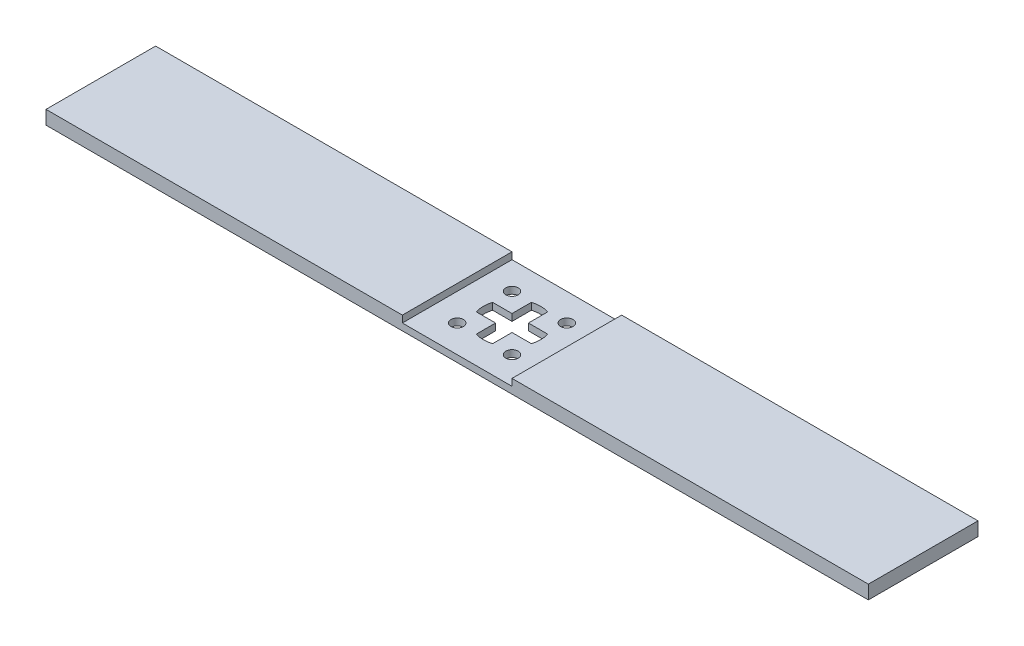
SolidWorks part; units mm, degrees
ref_plane "Front Plane" through (0, 0, 0) normal (0, 0, 1) x (1, 0, 0)
ref_plane "Top Plane" through (0, 0, 0) normal (0, 1, 0) x (1, 0, 0)
ref_plane "Right Plane" through (0, 0, 0) normal (1, 0, 0) x (0, 0, -1)
sketch "Sketch1" plane through (0, 0, 0) normal (0, 1, 0) x (1, 0, 0)
  line L0 (0, -32.4512) -> (0, 39.5498) construction
  line L1 (-150, 20) -> (150, 20)
  line L2 (-150, 20) -> (-150, -20)
  line L3 (-150, -20) -> (150, -20)
  line L4 (150, 20) -> (150, -20)
  line L5 (-150, 20) -> (150, -20) construction
  line L6 (-150, -20) -> (150, 20) construction
  line L7 (-19.3693, 0) -> (17.7156, 0) construction
  line L8 (-2.5, -2.5) -> (-2.5, -9.6825) construction
  line L9 (2.5, -9.6825) -> (2.5, -2.5) construction
  line L10 (2.5, -2.5) -> (9.6825, -2.5) construction
  line L11 (9.6825, 2.5) -> (2.5, 2.5) construction
  line L12 (2.5, 2.5) -> (2.5, 9.6825) construction
  line L13 (-2.5, 9.6825) -> (-2.5, 2.5) construction
  line L14 (-2.5, 2.5) -> (-9.6825, 2.5) construction
  line L15 (-9.6825, -2.5) -> (-2.5, -2.5) construction
  line L16 (-3, -3) -> (-3, -10.0623)
  line L17 (3, -10.0623) -> (3, -3)
  line L18 (3, -3) -> (10.0623, -3)
  line L19 (10.0623, 3) -> (3, 3)
  line L20 (3, 3) -> (3, 10.0623)
  line L21 (-3, 10.0623) -> (-3, 3)
  line L22 (-3, 3) -> (-10.0623, 3)
  line L23 (-10.0623, -3) -> (-3, -3)
  circle A0 centre (10, -10) radius 2.25
  circle A1 centre (10, 10) radius 2.25
  circle A2 centre (-10, -10) radius 2.25
  circle A3 centre (-10, 10) radius 2.25
  arc A4 (-2.5, -9.6825) -> (2.5, -9.6825) centre (0, 0) ccw construction
  arc A5 (9.6825, -2.5) -> (9.6825, 2.5) centre (0, 0) ccw construction
  arc A6 (2.5, 9.6825) -> (-2.5, 9.6825) centre (0, 0) ccw construction
  arc A7 (-9.6825, 2.5) -> (-9.6825, -2.5) centre (0, 0) ccw construction
  arc A8 (-3, -10.0623) -> (3, -10.0623) centre (0, 0) ccw
  arc A9 (10.0623, -3) -> (10.0623, 3) centre (0, 0) ccw
  arc A10 (3, 10.0623) -> (-3, 10.0623) centre (0, 0) ccw
  arc A11 (-10.0623, 3) -> (-10.0623, -3) centre (0, 0) ccw
  arc A12 (-2.5, -9.6825) -> (2.5, -9.6825) centre (0, 0) ccw construction
  point P0 (0, 0)
  dimension "D3" = 4.5
  dimension "D9" = 10.5
  dimension "D1" = 40
  dimension "D2" = 300
  dimension "D4" = 10
  dimension "D5" = 10
  dimension "D7" = 6
  dimension "D8" = 6
  dimension "D6" = 0.5
extrude "Boss-Extrude1" add sketch "Sketch1" along normal mid plane 5
sketch "Sketch2" plane through (0, 0, 20) normal (0, 0, 1) x (1, 0, 0)
  line L0 (0, 23.7336) -> (0, -22.5376) construction
  line L1 (-20, 2.5) -> (-20, 0)
  line L2 (-150, 2.5) -> (150, 2.5) construction
  line L3 (-20, 0) -> (20, 0)
  line L4 (20, 0) -> (20, 2.5)
  line L5 (-20, 2.5) -> (20, 2.5)
  dimension "D1" = 40
extrude "Cut-Extrude1" cut sketch "Sketch2" against normal through all
